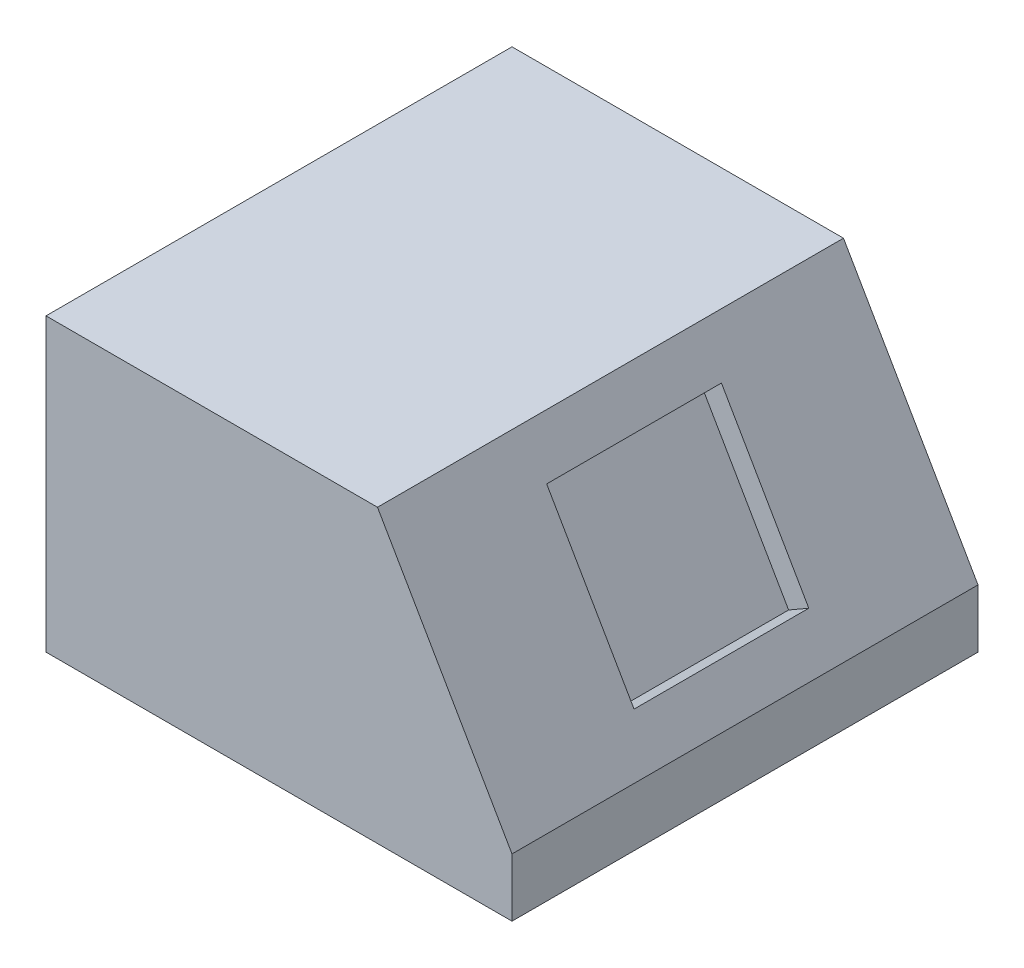
SolidWorks part; units mm, degrees
ref_plane "Plan de face" through (0, 0, 0) normal (0, 0, 1) x (1, 0, 0)
ref_plane "Plan de dessus" through (0, 0, 0) normal (0, 1, 0) x (1, 0, 0)
ref_plane "Plan de droite" through (0, 0, 0) normal (1, 0, 0) x (0, 0, -1)
sketch "Esquisse1" plane through (0, 0, 0) normal (0, 1, 0) x (1, 0, 0)
  line L1 (20, -20) -> (-20, -20)
  line L2 (20, -20) -> (20, 20)
  line L3 (20, 20) -> (-20, 20)
  line L4 (-20, -20) -> (-20, 20)
  line L5 (20, -20) -> (-20, 20) construction
  line L6 (20, 20) -> (-20, -20) construction
  point P0 (0, 0)
  dimension "D1" = 40
  dimension "D2" = 40
extrude "Boss.-Extru.1" add sketch "Esquisse1" along normal blind 25
chamfer "Chanfrein1" distance 20 angle 30 1 edges at (20, 25, 0)
sketch "Esquisse2" plane through (17.1651, 9.9103, 0) normal (0.866, 0.5, 0) x (0, 0, -1)
  line L0 (-20, -5.6699) -> (-20, 17.4241) construction
  line L1 (7.5, -1.6229) -> (-7.5, -1.6229)
  line L2 (7.5, -1.6229) -> (7.5, 13.3771)
  line L3 (7.5, 13.3771) -> (-7.5, 13.3771)
  line L4 (-7.5, -1.6229) -> (-7.5, 13.3771)
  line L5 (7.5, -1.6229) -> (-7.5, 13.3771) construction
  line L6 (7.5, 13.3771) -> (-7.5, -1.6229) construction
  point P0 (0, 5.8771)
  point P10 (-20, 5.8771)
  dimension "D1" = 15
  dimension "D2" = 15
extrude "Enlèv. mat.-Extru.1" cut sketch "Esquisse2" against normal blind 2
